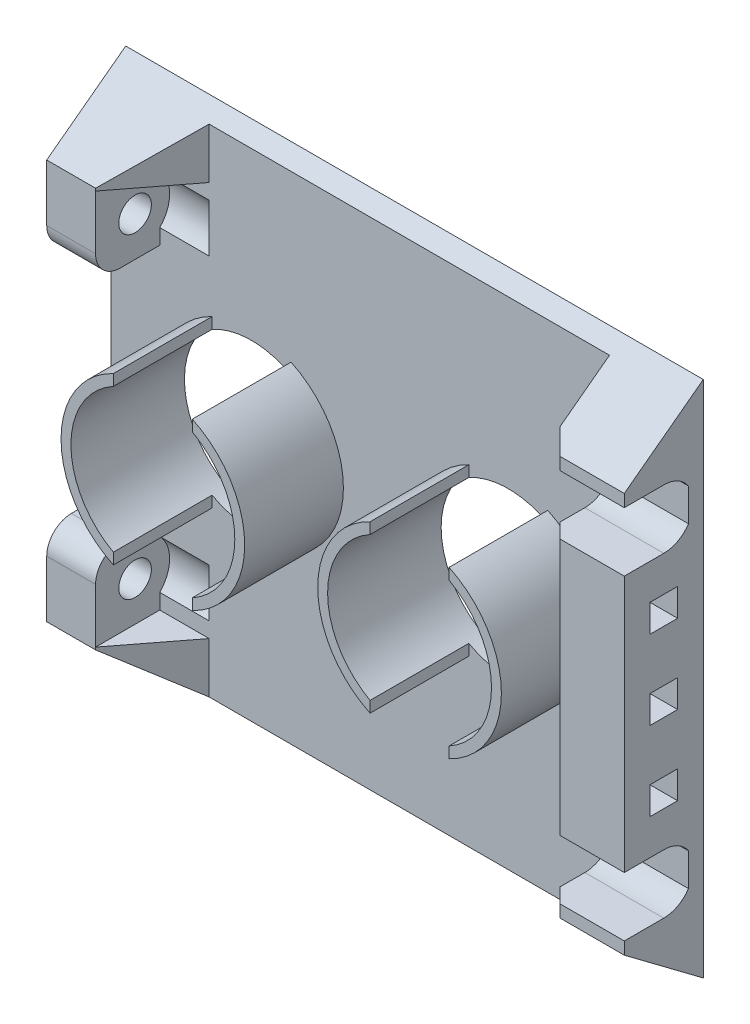
SolidWorks part; units mm, degrees
ref_plane "Plano frontal" through (0, 0, 0) normal (0, 0, 1) x (1, 0, 0)
ref_plane "Plano superior" through (0, 0, 0) normal (0, 1, 0) x (1, 0, 0)
ref_plane "Plano direito" through (0, 0, 0) normal (1, 0, 0) x (0, 0, -1)
sketch "Esboço1" plane through (0, 0, 0) normal (0, 0, 1) x (1, 0, 0)
  line L0 (-5, 0) -> (5, 0) construction
  line L1 (25, 0) -> (-25, 0) construction
  line L2 (0, 0) -> (0, -12.5) construction
  line L3 (25, -12.5) -> (-25, -12.5) construction
  line L4 (-21, 0) -> (-5, 0) construction
  line L5 (-25, -12.5) -> (-25, 12.5)
  line L6 (-25, 12.5) -> (25, 12.5)
  line L7 (0, 12.5) -> (0, 0) construction
  line L8 (20, -12.5) -> (-20, -12.5) construction
  line L12 (-15, -12.5) -> (15, -12.5)
  line L23 (21, 0) -> (5, 0) construction
  line L31 (25, -12.5) -> (25, 12.5)
  line L32 (-25, -12.5) -> (-15, -12.5)
  line L33 (15, -12.5) -> (25, -12.5)
  circle A0 centre (-13, 0) radius 8.3
  circle A1 centre (13, 0) radius 8.3
extrude "Ressalto-extrusão1" add sketch "Esboço1" along normal blind 1.5
sketch "Esboço2" plane through (0, 0, 1.5) normal (0, 0, 1) x (1, 0, 0)
  line L0 (-20, -12.5) -> (-25, -12.5)
  line L1 (0, -12.5) -> (0, 12.5) construction
  line L2 (20, -12.5) -> (-20, -12.5) construction
  line L3 (-25, -12.5) -> (25, -12.5) construction
  line L4 (22, -2.5) -> (22, -9.5)
  line L5 (-25, 12.5) -> (-25, -12.5) construction
  line L6 (-22, -9.5) -> (-15, -9.5)
  line L7 (-15, -9.5) -> (-15, -12.5)
  line L8 (-15, -12.5) -> (-20, -12.5)
  line L9 (-25, -12.5) -> (-25, -2.5)
  line L10 (-25, -2.5) -> (-22, -2.5)
  line L11 (-22, -2.5) -> (-22, -9.5)
  line L12 (25, -2.5) -> (22, -2.5)
  line L13 (25, -12.5) -> (25, -2.5)
  line L14 (15, -12.5) -> (20, -12.5)
  line L15 (25, 12.5) -> (-25, 12.5) construction
  line L16 (15, -9.5) -> (15, -12.5)
  line L17 (-25, 0) -> (25, 0) construction
  line L18 (25, -12.5) -> (25, 12.5) construction
  line L19 (22, -9.5) -> (15, -9.5)
  line L20 (20, -12.5) -> (25, -12.5)
  line L21 (20, 12.5) -> (-20, 12.5) construction
  line L22 (20, 12.5) -> (25, 12.5)
  line L23 (22, 9.5) -> (15, 9.5)
  line L24 (15, 9.5) -> (15, 12.5)
  line L25 (15, 12.5) -> (20, 12.5)
  line L26 (25, 12.5) -> (25, 2.5)
  line L27 (25, 2.5) -> (22, 2.5)
  line L28 (-22, 2.5) -> (-22, 9.5)
  line L29 (-25, 2.5) -> (-22, 2.5)
  line L30 (-25, 12.5) -> (-25, 2.5)
  line L31 (-15, 12.5) -> (-20, 12.5)
  line L32 (-15, 9.5) -> (-15, 12.5)
  line L33 (-22, 9.5) -> (-15, 9.5)
  line L34 (22, 2.5) -> (22, 9.5)
  line L35 (-20, 12.5) -> (-25, 12.5)
extrude "Ressalto-extrusão2" add sketch "Esboço2" along normal blind 6
sketch "Esboço3" plane through (0, -12.5, 0) normal (0, -1, 0) x (1, 0, 0)
  line L0 (-25, 3.75) -> (-15, 3.75) construction
  line L1 (-25, 7.5) -> (-25, 0) construction
  line L2 (-15, 7.5) -> (-15, 1.5) construction
  line L3 (-15, 3.75) -> (-20, 3.75) construction
  line L4 (-20, 3.75) -> (-20, 7.5) construction
  line L5 (-25, 7.5) -> (-15, 7.5) construction
  line L6 (0, 0) -> (0, 8.9122) construction
  line L7 (-21.4, 2.35) -> (-18.6, 2.35)
  line L8 (-21.4, 2.35) -> (-21.4, 5.15)
  line L9 (-21.4, 5.15) -> (-18.6, 5.15)
  line L10 (-18.6, 2.35) -> (-18.6, 5.15)
  line L11 (-21.4, 2.35) -> (-18.6, 5.15) construction
  line L12 (-21.4, 5.15) -> (-18.6, 2.35) construction
  line L13 (-25, 0) -> (25, 0) construction
  line L14 (21.4, 5.15) -> (18.6, 2.35) construction
  line L15 (21.4, 2.35) -> (18.6, 5.15) construction
  line L16 (18.6, 2.35) -> (18.6, 5.15)
  line L17 (21.4, 5.15) -> (18.6, 5.15)
  line L18 (21.4, 2.35) -> (21.4, 5.15)
  line L19 (21.4, 2.35) -> (18.6, 2.35)
extrude "Corte-extrusão1" cut sketch "Esboço3" against normal through all
sketch "Esboço4" plane through (-25, 0, 0) normal (-1, 0, 0) x (0, 0, 1)
  line L2 (3.75, 2.5) -> (3.75, 12.5) construction
  line L5 (3.75, -2.5) -> (3.75, -12.5) construction
  line L9 (0, 12.5) -> (7.5, 12.5) construction
  line L10 (5.15, 8.9) -> (2.35, 8.9)
  line L11 (5.15, 8.9) -> (5.15, 6.1)
  line L12 (5.15, 6.1) -> (2.35, 6.1)
  line L13 (2.35, 8.9) -> (2.35, 6.1)
  line L14 (5.15, 8.9) -> (2.35, 6.1) construction
  line L15 (5.15, 6.1) -> (2.35, 8.9) construction
  line L16 (5.15, -6.1) -> (2.35, -6.1)
  line L17 (5.15, -6.1) -> (5.15, -8.9)
  line L18 (5.15, -8.9) -> (2.35, -8.9)
  line L19 (2.35, -6.1) -> (2.35, -8.9)
  line L20 (5.15, -6.1) -> (2.35, -8.9) construction
  line L21 (5.15, -8.9) -> (2.35, -6.1) construction
  point P12 (3.75, 7.5)
  point P17 (3.75, -7.5)
  point P26 (3.75, 12.5)
extrude "Corte-extrusão2" cut sketch "Esboço4" against normal through all
sketch "Esboço6" plane through (0, 0, 0) normal (0, 0, -1) x (-1, 0, 0)
  line L0 (-25, 12.5) -> (-25, -12.5)
  line L1 (-30, -12.5) -> (-25, -12.5)
  line L2 (-30, -12.5) -> (-30, 12.5)
  line L3 (-30, 12.5) -> (-25, 12.5)
  line L4 (30, -12.5) -> (30, 12.5)
  line L5 (-30, -12.5) -> (30, 12.5) construction
  line L6 (-30, 12.5) -> (30, -12.5) construction
  line L7 (25, 12.5) -> (25, -12.5)
  line L8 (25, 12.5) -> (30, 12.5)
  line L9 (25, -12.5) -> (30, -12.5)
  point P0 (0, 0)
extrude "Ressalto-extrusão5" add sketch "Esboço6" against normal up to surface (7.5 mm away) up to face at (20.6667, -8.1667, 7.5)
sketch "Esboço7" plane through (30, 0, 0) normal (1, 0, 0) x (0, 0, -1)
  line L0 (-2.35, -6.1) -> (-5.15, -6.1) construction
  line L1 (-2.35, -8.9) -> (-2.35, -6.1) construction
  line L2 (-5.15, -8.9) -> (-2.35, -8.9) construction
  line L3 (-5.15, -6.1) -> (-5.15, -8.9) construction
  line L4 (-2.35, -6.1) -> (-5.15, -6.1)
  line L5 (-2.35, -8.9) -> (-2.35, -6.1)
  line L6 (-5.15, -8.9) -> (-2.35, -8.9)
  line L7 (-5.15, -6.1) -> (-5.15, -8.9)
  line L8 (-2.35, 6.1) -> (-2.35, 8.9) construction
  line L9 (-2.35, 8.9) -> (-5.15, 8.9) construction
  line L10 (-5.15, 8.9) -> (-5.15, 6.1) construction
  line L11 (-5.15, 6.1) -> (-2.35, 6.1) construction
  line L12 (-2.35, 6.1) -> (-2.35, 8.9)
  line L13 (-2.35, 8.9) -> (-5.15, 8.9)
  line L14 (-5.15, 8.9) -> (-5.15, 6.1)
  line L15 (-5.15, 6.1) -> (-2.35, 6.1)
extrude "Corte-extrusão3" cut sketch "Esboço7" against normal up to surface (60 mm away) up to face at (-30, 0, 3.75)
sketch "Esboço5" plane through (0, 0, 1.5) normal (0, 0, 1) x (1, 0, 0)
  line L0 (-9, -7.2726) -> (-9, -8.3958)
  line L1 (-17, -7.2726) -> (-17, -8.3958)
  line L2 (-17, 8.3958) -> (-17, 7.2726)
  line L3 (9, -7.2726) -> (9, -8.3958)
  line L4 (-9, 8.3958) -> (-9, 7.2726)
  line L8 (17, 8.3958) -> (17, 7.2726)
  line L10 (9, 8.3958) -> (9, 7.2726)
  line L13 (17, -7.2726) -> (17, -8.3958)
  circle A0 centre (-13, 0) radius 8.3 construction
  circle A1 centre (13, 0) radius 8.3 construction
  arc A2 (-17, 7.2726) -> (-17, -7.2726) centre (-13, 0) ccw
  arc A3 (17, -7.2726) -> (17, 7.2726) centre (13, 0) ccw
  arc A4 (-17, 8.3958) -> (-17, -8.3958) centre (-13, 0) ccw
  arc A5 (17, -8.3958) -> (17, 8.3958) centre (13, 0) ccw
  circle A6 centre (-13, 0) radius 8.3 construction
  circle A7 centre (-13, 0) radius 9.3 construction
  circle A8 centre (13, 0) radius 8.3 construction
  circle A9 centre (13, 0) radius 9.3 construction
  arc A12 (-9, -8.3958) -> (-9, 8.3958) centre (-13, 0) ccw
  arc A13 (-9, -7.2726) -> (-9, 7.2726) centre (-13, 0) ccw
  arc A14 (9, 7.2726) -> (9, -7.2726) centre (13, 0) ccw
  arc A15 (9, 8.3958) -> (9, -8.3958) centre (13, 0) ccw
  dimension "D1" = 1
  dimension "D2" = 1
extrude "Ressalto-extrusão3" add sketch "Esboço5" along normal blind 10
sketch "Esboço8" plane through (0, 0, 0) normal (0, 0, -1) x (-1, 0, 0)
  line L1 (30, 26.25) -> (-30, 26.25)
  line L2 (30, 26.25) -> (30, -26.25)
  line L3 (30, -26.25) -> (-30, -26.25)
  line L4 (-30, 26.25) -> (-30, -26.25)
  line L5 (30, 26.25) -> (-30, -26.25) construction
  line L6 (30, -26.25) -> (-30, 26.25) construction
  circle A0 centre (13, 0) radius 8.3
  circle A1 centre (-13, 0) radius 8.3
  point P6 (0, 0)
extrude "Ressalto-extrusão6" add sketch "Esboço8" against normal blind 1.5
sketch "Esboço9" plane through (0, 0, 1.5) normal (0, 0, 1) x (1, 0, 0)
  line L12 (-15, -12.5) -> (-15, -9.5)
  line L13 (-15, -9.5) -> (-22, -9.5)
  line L14 (-22, -9.5) -> (-22, -2.5)
  line L15 (-22, -2.5) -> (-25, -2.5)
  line L16 (-25, -2.5) -> (-25, 2.5)
  line L17 (-25, 2.5) -> (-22, 2.5)
  line L18 (-22, 2.5) -> (-22, 9.5)
  line L19 (-22, 9.5) -> (-15, 9.5)
  line L20 (-15, 9.5) -> (-15, 12.5)
  line L21 (-15, 12.5) -> (-30, 12.5)
  line L22 (-30, 12.5) -> (-30, -12.5)
  line L23 (-30, -12.5) -> (-15, -12.5)
  line L24 (-15, -12.5) -> (-15, -9.5)
  line L25 (-15, -9.5) -> (-22, -9.5)
  line L26 (-22, -9.5) -> (-22, -2.5)
  line L27 (-22, -2.5) -> (-25, -2.5)
  line L28 (-25, -2.5) -> (-25, 2.5)
  line L29 (-25, 2.5) -> (-22, 2.5)
  line L30 (-22, 2.5) -> (-22, 9.5)
  line L31 (-22, 9.5) -> (-15, 9.5)
  line L32 (-15, 9.5) -> (-15, 12.5)
  line L33 (-15, 12.5) -> (-30, 12.5)
  line L34 (-30, 12.5) -> (-30, -12.5)
  line L35 (-30, -12.5) -> (-15, -12.5)
  dimension "D1" = 0
extrude "Corte-extrusão4" cut sketch "Esboço9" along normal through all
sketch "Esboço10" plane through (0, 0, 1.5) normal (0, 0, 1) x (1, 0, 0)
  line L0 (-24.3, -26.25) -> (-24.3, 26.25)
  line L2 (-24.3, 26.25) -> (-22.3, 26.25)
  line L4 (-22.3, 12) -> (-17.3, 12)
  line L5 (-17.3, 12) -> (-17.3, -12)
  line L6 (-17.3, 0) -> (-24.3, 0) construction
  line L7 (-22.3, 20) -> (-22.3, 12)
  line L8 (-22.3, -20) -> (-22.3, -12)
  line L9 (-22.3, -12) -> (-17.3, -12)
  line L10 (-24.3, -26.25) -> (-22.3, -26.25)
  line L11 (-22.3, 12) -> (-22.3, 16) construction
  line L12 (-22.3, 16) -> (-22.3, 20) construction
  line L13 (-22.3, 20) -> (-17.3, 20)
  line L14 (-17.3, 20) -> (-17.3, 26.25)
  line L15 (-17.3, 26.25) -> (-22.3, 26.25)
  line L16 (-17.3, -26.25) -> (-22.3, -26.25)
  line L17 (-17.3, -20) -> (-17.3, -26.25)
  line L18 (-22.3, -20) -> (-17.3, -20)
  line L19 (-24.3, 0) -> (-22.3, 0) construction
  arc A0 (-17, 8.3958) -> (-17, -8.3958) centre (-13, 0) ccw construction
  point P22 (-22.3, 0)
  dimension "D1" = 12
extrude "Ressalto-extrusão7" add sketch "Esboço10" along normal blind 6.5
sketch "Esboço11" plane through (0, -26.25, 0) normal (0, -1, 0) x (1, 0, 0)
  line L0 (-22.3, 8) -> (-17.3, 8)
  line L1 (-17.3, 8) -> (-17.3, 1.5)
  line L2 (-22.3, 8) -> (-17.3, 1.5)
sketch "Esboço12" plane through (-24.3, 0, 0) normal (-1, 0, 0) x (0, 0, 1)
  line L0 (4, 0) -> (4, 16) construction
  line L1 (0, -26.25) -> (0, 26.25) construction
  line L3 (0, 0) -> (8, 0) construction
  circle A0 centre (4, 16) radius 1.65
  circle A1 centre (4, -16) radius 1.65
  dimension "D1" = 4
sketch "Esboço14" plane through (0, 0, 1.5) normal (0, 0, 1) x (1, 0, 0)
  line L4 (-30, -26.25) -> (-24.3, -26.25)
  line L5 (-24.3, -26.25) -> (-24.3, 26.25)
  line L6 (-24.3, 26.25) -> (-30, 26.25)
  line L7 (-30, 26.25) -> (-30, -26.25)
  line L8 (-30, -26.25) -> (-24.3, -26.25)
  line L9 (-24.3, -26.25) -> (-24.3, 26.25)
  line L10 (-24.3, 26.25) -> (-30, 26.25)
  line L11 (-30, 26.25) -> (-30, -26.25)
  dimension "D1" = 0
extrude "Corte-extrusão8" cut sketch "Esboço14" against normal blind 4.5
sketch "Esboço15" plane through (0, 0, 8) normal (0, 0, 1) x (1, 0, 0)
  line L1 (-17.3, -7.0993) -> (-17.3, 7.0993)
  line L2 (-17.3, -7.0993) -> (-17.3, 7.0993)
  arc A1 (-17.3, 7.0993) -> (-17.3, -7.0993) centre (-13, 0) ccw
  arc A2 (-17.3, 7.0993) -> (-17.3, -7.0993) centre (-13, 0) ccw
  dimension "D1" = 0
extrude "Corte-extrusão9" cut sketch "Esboço15" against normal through all
extrude "Corte-extrusão13" cut sketch "Esboço11" against normal up to surface (6.25 mm away) up to face at (-19.8, -20, 4.75)
sketch "Esboço17" plane through (0, 26.25, 0) normal (0, 1, 0) x (1, 0, 0)
  line L0 (-17.3, -1.5) -> (-17.3, -8)
  line L1 (-17.3, -8) -> (-22.3, -8)
  line L2 (-17.3, -8) -> (-24.3, -8) construction
  line L3 (-22.3, -8) -> (-17.3, -1.5)
extrude "Corte-extrusão14" cut sketch "Esboço17" against normal up to surface (6.25 mm away) up to face at (-19.8, 20, 4.75)
extrude "Corte-extrusão15" cut sketch "Esboço12" against normal blind 4.5
sketch "Esboço19" plane through (-24.3, 0, 0) normal (-1, 0, 0) x (0, 0, 1)
  line L0 (0, 26.25) -> (8, 26.25)
  line L1 (8, 26.25) -> (8, 20.25)
  line L2 (8, 26.25) -> (8, -26.25) construction
  line L3 (8, 20.25) -> (0, 26.25)
  line L4 (0, 0) -> (8, 0) construction
  line L5 (8, -20.25) -> (0, -26.25)
  line L6 (8, -26.25) -> (8, -20.25)
  line L7 (0, -26.25) -> (8, -26.25)
extrude "Corte-extrusão17" cut sketch "Esboço19" against normal through all
sketch "Esboço20" plane through (-22.3, 0, 0) normal (1, 0, 0) x (0, 0, -1)
  circle A0 centre (-4, -16) radius 3.5
  circle A1 centre (-4, 16) radius 3.5
extrude "Corte-extrusão18" cut sketch "Esboço20" along normal blind 5
sketch "Esboço21" plane through (-24.3, 0, 0) normal (-1, 0, 0) x (0, 0, 1)
  line L4 (0, 26.25) -> (0, -26.25)
  line L5 (0, -26.25) -> (8, -20.25)
  line L6 (8, -20.25) -> (8, 20.25)
  line L7 (8, 20.25) -> (0, 26.25)
  line L8 (0, 26.25) -> (0, -26.25)
  line L9 (0, -26.25) -> (8, -20.25)
  line L10 (8, -20.25) -> (8, 20.25)
  line L11 (8, 20.25) -> (0, 26.25)
  circle A0 centre (4, -16) radius 1.65 construction
  circle A1 centre (4, -16) radius 1.65
  circle A2 centre (4, 16) radius 1.65 construction
  circle A3 centre (4, 16) radius 1.65
  dimension "D1" = 0
extrude "Ressalto-extrusão8" add sketch "Esboço21" along normal blind 2.95
sketch "Esboço22" plane through (30, 0, 0) normal (1, 0, 0) x (0, 0, -1)
  line L0 (-2.35, -6.1) -> (-5.15, -6.1) construction
  line L1 (-2.35, -8.9) -> (-2.35, -6.1) construction
  line L2 (-5.15, -8.9) -> (-2.35, -8.9) construction
  line L3 (-5.15, -6.1) -> (-5.15, -8.9) construction
  line L4 (-2.35, 8.9) -> (-5.15, 8.9) construction
  line L5 (-5.15, 8.9) -> (-5.15, 6.1) construction
  line L6 (-2.35, 6.1) -> (-2.35, 8.9) construction
  line L7 (-5.15, 6.1) -> (-2.35, 6.1) construction
  line L8 (-1.5, -25.125) -> (0, -26.25)
  line L9 (0, -26.25) -> (0, 26.25)
  line L10 (0, 26.25) -> (-1.5, 25.125)
  line L11 (-1.5, 25.125) -> (-1.5, 12.5)
  line L12 (-1.5, 12.5) -> (-7.5, 12.5)
  line L13 (-7.5, 12.5) -> (-7.5, -12.5)
  line L14 (-7.5, -12.5) -> (-1.5, -12.5)
  line L15 (-1.5, -12.5) -> (-1.5, -25.125)
  line L16 (-1.5, -25.125) -> (0, -26.25)
  line L17 (0, -26.25) -> (0, 26.25)
  line L18 (0, 26.25) -> (-1.5, 25.125)
  line L19 (-1.5, 25.125) -> (-1.5, 12.5)
  line L20 (-1.5, 12.5) -> (-7.5, 12.5)
  line L21 (-7.5, 12.5) -> (-7.5, -12.5)
  line L22 (-7.5, -12.5) -> (-1.5, -12.5)
  line L23 (-1.5, -12.5) -> (-1.5, -25.125)
  line L24 (-2.35, -6.1) -> (-5.15, -6.1)
  line L25 (-2.35, -8.9) -> (-2.35, -6.1)
  line L26 (-5.15, -8.9) -> (-2.35, -8.9)
  line L27 (-5.15, -6.1) -> (-5.15, -8.9)
  line L28 (-2.35, 8.9) -> (-5.15, 8.9)
  line L29 (-5.15, 8.9) -> (-5.15, 6.1)
  line L30 (-2.35, 6.1) -> (-2.35, 8.9)
  line L31 (-5.15, 6.1) -> (-2.35, 6.1)
  dimension "D1" = 0
extrude "Ressalto-extrusão9" add sketch "Esboço22" along normal blind 1.25
sketch "Esboço23" plane through (0, 0, 7.5) normal (0, 0, 1) x (1, 0, 0)
  line L12 (25, -2.5) -> (22, -2.5)
  line L13 (22, -2.5) -> (22, -9.5)
  line L14 (22, -9.5) -> (15, -9.5)
  line L15 (15, -9.5) -> (15, -12.5)
  line L16 (15, -12.5) -> (31.25, -12.5)
  line L17 (31.25, -12.5) -> (31.25, 12.5)
  line L18 (31.25, 12.5) -> (15, 12.5)
  line L19 (15, 12.5) -> (15, 9.5)
  line L20 (15, 9.5) -> (22, 9.5)
  line L21 (22, 9.5) -> (22, 2.5)
  line L22 (22, 2.5) -> (25, 2.5)
  line L23 (25, 2.5) -> (25, -2.5)
  line L24 (25, -2.5) -> (22, -2.5)
  line L25 (22, -2.5) -> (22, -9.5)
  line L26 (22, -9.5) -> (15, -9.5)
  line L27 (15, -9.5) -> (15, -12.5)
  line L28 (15, -12.5) -> (31.25, -12.5)
  line L29 (31.25, -12.5) -> (31.25, 12.5)
  line L30 (31.25, 12.5) -> (15, 12.5)
  line L31 (15, 12.5) -> (15, 9.5)
  line L32 (15, 9.5) -> (22, 9.5)
  line L33 (22, 9.5) -> (22, 2.5)
  line L34 (22, 2.5) -> (25, 2.5)
  line L35 (25, 2.5) -> (25, -2.5)
  dimension "D1" = 0
extrude "Corte-extrusão19" cut sketch "Esboço23" against normal up to surface (6 mm away) up to face at (13, 0, 1.5)
sketch "Esboço24" plane through (0, 0, 1.5) normal (0, 0, 1) x (1, 0, 0)
  line L0 (31.25, -25.125) -> (-17.3, -25.125) construction
  line L1 (31.25, 25.125) -> (23.25, 25.125)
  line L2 (31.25, 25.125) -> (31.25, -25.125)
  line L3 (31.25, -25.125) -> (23.25, -25.125)
  line L4 (23.25, 25.125) -> (23.25, -25.125)
extrude "Ressalto-extrusão10" add sketch "Esboço24" along normal up to surface (6.5 mm away) up to face at (-21.875, 0, 8)
sketch "Esboço25" plane through (0, 25.125, 0) normal (0, 1, 0) x (1, 0, 0)
  line L1 (23.25, -8) -> (23.25, -1.5) construction
  line L2 (23.25, -6.5) -> (23.25, -8)
  line L3 (23.25, -8) -> (24.75, -8)
  line L4 (23.25, -8) -> (31.25, -8) construction
  line L5 (24.75, -8) -> (23.25, -6.5)
extrude "Corte-extrusão20" cut sketch "Esboço25" against normal through all
sketch "Esboço26" plane through (31.25, 0, 0) normal (1, 0, 0) x (0, 0, -1)
  line L0 (-8, 0) -> (0, 0) construction
  line L1 (-8, 25.125) -> (-8, -25.125) construction
  line L2 (0, 0) -> (-4, 0) construction
  line L3 (-4, 0) -> (-4, -8) construction
  line L4 (-2.6, 1.4) -> (-5.4, 1.4)
  line L5 (-2.6, -6.6) -> (-5.4, -6.6)
  line L6 (-2.6, -6.6) -> (-2.6, -9.4)
  line L7 (-2.6, -9.4) -> (-5.4, -9.4)
  line L8 (-5.4, -6.6) -> (-5.4, -9.4)
  line L9 (-2.6, -6.6) -> (-5.4, -9.4) construction
  line L10 (-2.6, -9.4) -> (-5.4, -6.6) construction
  line L11 (-2.6, 1.4) -> (-2.6, -1.4)
  line L12 (-2.6, -1.4) -> (-5.4, -1.4)
  line L13 (-5.4, 1.4) -> (-5.4, -1.4)
  line L14 (-2.6, 1.4) -> (-5.4, -1.4) construction
  line L15 (-2.6, -1.4) -> (-5.4, 1.4) construction
  line L16 (-2.6, 9.4) -> (-5.4, 9.4)
  line L17 (-2.6, 9.4) -> (-2.6, 6.6)
  line L18 (-2.6, 6.6) -> (-5.4, 6.6)
  line L19 (-5.4, 9.4) -> (-5.4, 6.6)
  line L20 (-2.6, 9.4) -> (-5.4, 6.6) construction
  line L21 (-2.6, 6.6) -> (-5.4, 9.4) construction
  dimension "D1" = 3
extrude "Corte-extrusão21" cut sketch "Esboço26" against normal up to next
sketch "Esboço27" plane through (31.25, 0, 0) normal (1, 0, 0) x (0, 0, -1)
  line L0 (-4, 19) -> (-8, 19)
  line L1 (-8, -20.25) -> (-8, -25.125)
  line L2 (-8, 25.125) -> (-8, -25.125) construction
  line L3 (-8, 25.125) -> (-8, 20.25)
  line L4 (-8, 19) -> (-8, 13)
  line L5 (-8, 13) -> (-4, 13)
  line L6 (-4, -13) -> (-8, -13)
  line L7 (-8, -13) -> (-8, -19)
  line L8 (-8, -19) -> (-4, -19)
  line L9 (-1.5, 25.125) -> (-1.5, -25.125) construction
  line L10 (-1.5, 17.6583) -> (-1.5, 14.3417)
  line L11 (-1.5, -14.3417) -> (-1.5, -17.6583)
  line L13 (-1.5, 25.125) -> (-8, 20.25) construction
  line L17 (-8, -20.25) -> (-1.5, -25.125) construction
  line L21 (-1.5, 25.125) -> (-8, 20.25)
  line L25 (-8, -20.25) -> (-1.5, -25.125)
  line L28 (-1.5, 25.125) -> (-8, 25.125)
  line L30 (-1.5, -25.125) -> (-8, -25.125)
  circle A0 centre (-4, -16) radius 1.65 construction
  circle A1 centre (-4, 16) radius 1.65 construction
  circle A2 centre (-4, -16) radius 1.65 construction
  circle A3 centre (-4, 16) radius 1.65 construction
  arc A4 (-4, -19) -> (-1.5, -17.6583) centre (-4, -16) ccw
  arc A5 (-4, 13) -> (-1.5, 14.3417) centre (-4, 16) ccw
  arc A6 (-1.5, 17.6583) -> (-4, 19) centre (-4, 16) ccw
  arc A7 (-1.5, -14.3417) -> (-4, -13) centre (-4, -16) ccw
extrude "Corte-extrusão22" cut sketch "Esboço27" against normal up to next
sketch "Esboço28" plane through (0, 0, 8) normal (0, 0, 1) x (1, 0, 0)
  line L0 (-27.25, -12) -> (-27.25, 12)
  line L1 (-27.25, -20.25) -> (-27.25, 20.25) construction
  line L2 (-27.25, 12) -> (-24.8, 12)
  line L3 (-22.3, 9.5) -> (-22.3, -9.5)
  line L4 (-24.8, -12) -> (-27.25, -12)
  line L5 (-27.25, -12) -> (-27.25, 12)
  arc A0 (-24.8, 12) -> (-22.3, 9.5) centre (-24.8, 9.5) cw
  arc A1 (-22.3, -9.5) -> (-24.8, -12) centre (-24.8, -9.5) cw
  point P9 (-22.3, 12)
  line M2 (-27.25, 20.25) -> (-27.25, -20.25)
  dimension "D1" = 2.5
extrude "Corte-extrusão23" cut sketch "Esboço28" against normal up to surface (6.5 mm away) contours A1 L3 A0 L2 L4 M2 up to face at (13, 0, 1.5)
sketch "Esboço29" plane through (0, 0, 8) normal (0, 0, 1) x (1, 0, 0)
  line L0 (-19.8, -12) -> (-19.8, -12.4492)
  line L6 (-19.8, 12) -> (-19.8, 12.9071)
  line L7 (-19.8, 12.9071) -> (-15.7505, 12.9071)
  line L8 (-15.7505, 12.9071) -> (-15.7505, 9.5)
  line L9 (-15.7505, 9.5) -> (-17.3, 9.5)
  line L10 (-17.3, -9.5) -> (-15.2259, -9.5)
  line L11 (-15.2259, -9.5) -> (-15.2259, -14.1397)
  line L12 (-15.2259, -14.1397) -> (-19.8, -14.1397)
  line L13 (-19.8, -14.1397) -> (-19.8, -12.4492)
  arc A0 (-19.8, -12) -> (-17.3, -9.5) centre (-19.8, -9.5) ccw
  arc A1 (-19.8, 12) -> (-17.3, 9.5) centre (-19.8, 9.5) cw
  point P16 (-17.3, -12)
  point P19 (-17.3, 12)
  dimension "D1" = 2.5
extrude "Corte-extrusão24" cut sketch "Esboço29" against normal up to surface (6.5 mm away) up to face at (13, 0, 1.5)
sketch "Esboço30" plane through (0, 0, 8) normal (0, 0, 1) x (1, 0, 0)
  line L0 (-27.25, 12) -> (-17, 12)
  line L1 (-17, 12) -> (-17, 8.3958)
  line L2 (-27.25, -12) -> (-17, -12)
  line L3 (-17, -12) -> (-17, -8.3958)
  line L4 (-27.25, -12) -> (-27.25, 12)
  arc A0 (-17, 8.3958) -> (-17, -8.3958) centre (-13, 0) ccw construction
  arc A1 (-17, 8.3958) -> (-17, -8.3958) centre (-13, 0) ccw
extrude "Corte-extrusão25" cut sketch "Esboço30" against normal up to surface (6.5 mm away) up to face at (-6.4691, 0, 1.5)
sketch "Esboço31" plane through (-27.25, 0, 0) normal (-1, 0, 0) x (0, 0, 1)
  line L8 (5.5, -12) -> (8, -12)
  line L9 (8, -12) -> (8, -14.5)
  line L10 (5.5, 12) -> (8, 12)
  line L11 (8, 12) -> (8, 14.5)
  arc A0 (5.5, -12) -> (8, -14.5) centre (5.5, -14.5) cw
  arc A1 (5.5, 12) -> (8, 14.5) centre (5.5, 14.5) ccw
  point P18 (8, -12)
  point P21 (8, 12)
  dimension "D1" = 2.5
extrude "Corte-extrusão26" cut sketch "Esboço31" against normal up to surface (4.95 mm away) up to face at (-22.3, 16, 5.65)
